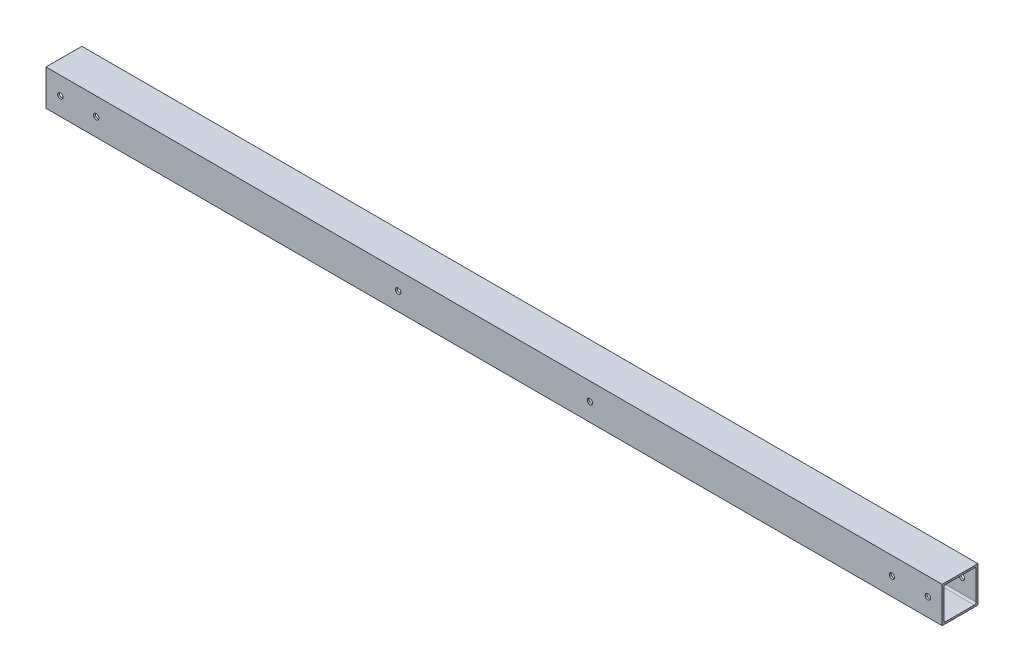
SolidWorks part; units mm, degrees
material "Thornel Mat VMA"
ref_plane "Front Plane" through (0, 0, 0) normal (0, 0, 1) x (1, 0, 0)
ref_plane "Top Plane" through (0, 0, 0) normal (0, 1, 0) x (1, 0, 0)
ref_plane "Right Plane" through (0, 0, 0) normal (1, 0, 0) x (0, 0, -1)
sketch "Sketch1" plane through (0, 0, 0) normal (1, 0, 0) x (0, 0, -1)
  line L1 (-8, -9) -> (8, -9)
  line L2 (-9, -8) -> (-9, 8)
  line L3 (-8, 9) -> (8, 9)
  line L4 (9, -8) -> (9, 8)
  line L5 (-9, -9) -> (9, 9) construction
  line L6 (-9, 9) -> (9, -9) construction
  line L7 (-10, -10) -> (10, -10)
  line L8 (-10, -10) -> (-10, 10)
  line L9 (-10, 10) -> (10, 10)
  line L10 (10, -10) -> (10, 10)
  line L11 (-10, -10) -> (10, 10) construction
  line L12 (-10, 10) -> (10, -10) construction
  arc A0 (-8, -9) -> (-9, -8) centre (-8, -8) cw
  arc A1 (8, -9) -> (9, -8) centre (8, -8) ccw
  arc A2 (8, 9) -> (9, 8) centre (8, 8) cw
  arc A3 (-9, 8) -> (-8, 9) centre (-8, 8) cw
  point P0 (0, 0)
  point P6 (0, 0)
  dimension "D5" = 1
  dimension "D1" = 20
  dimension "D2" = 20
  dimension "D3" = 1
  dimension "D4" = 1
extrude "Boss-Extrude1" add sketch "Sketch1" along normal blind 500
sketch "Sketch2" plane through (0, 0, 10) normal (0, 0, 1) x (1, 0, 0)
  line L0 (0, 10) -> (0, -10) construction
  circle A0 centre (8, 0) radius 1.5
  circle A1 centre (28, 0) radius 1.5
  dimension "D1" = 3
  dimension "D2" = 3
  dimension "D3" = 20
  dimension "D4" = 8
extrude "Cut-Extrude1" cut sketch "Sketch2" against normal blind 600
sketch "Sketch3" plane through (0, 0, 10) normal (0, 0, 1) x (1, 0, 0)
  line L0 (500, 10) -> (500, -10) construction
  circle A0 centre (492, 0) radius 1.5
  circle A1 centre (472, 0) radius 1.5
  dimension "D1" = 20
  dimension "D2" = 8
  dimension "D3" = 3
  dimension "D4" = 3
extrude "Cut-Extrude2" cut sketch "Sketch3" against normal blind 30
sketch "Sketch4" plane through (0, 0, 10) normal (0, 0, 1) x (1, 0, 0)
  line L0 (500, 10) -> (500, -10) construction
  line L1 (0, 10) -> (0, -10) construction
  circle A0 centre (196.5, 0) radius 1.5
  circle A1 centre (303.5, 0) radius 1.5
  dimension "D1" = 196.5
  dimension "D2" = 196.5
  dimension "D3" = 3
  dimension "D4" = 3
extrude "Cut-Extrude3" cut sketch "Sketch4" against normal blind 20
